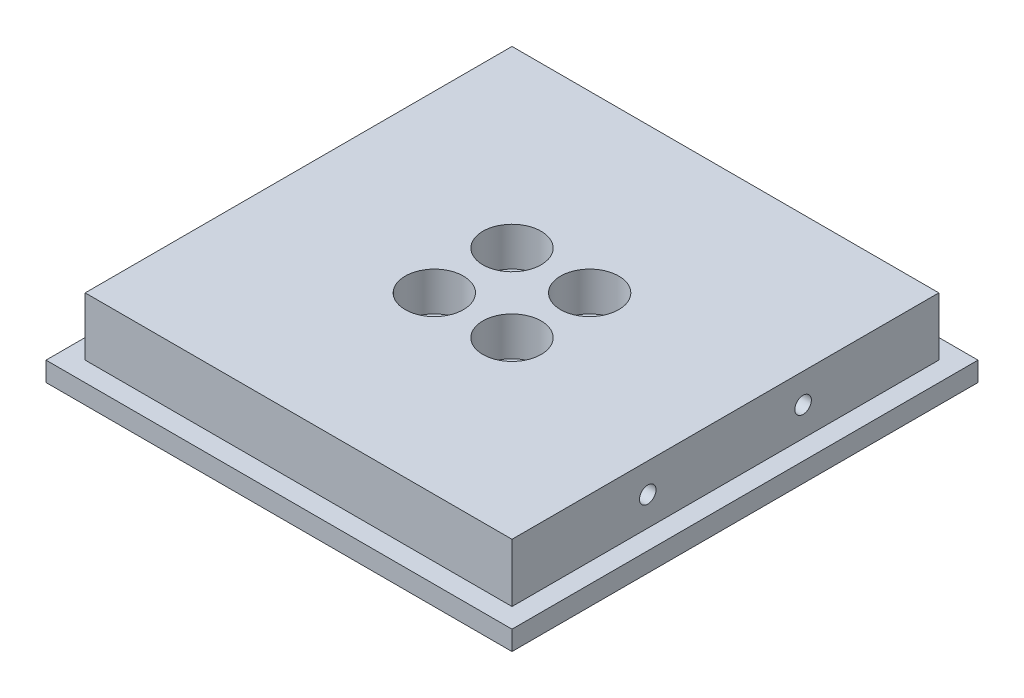
SolidWorks part; units mm, degrees
material "6061-T6 (SS)"
ref_plane "Front Plane" through (0, 0, 0) normal (0, 0, 1) x (1, 0, 0)
ref_plane "Top Plane" through (0, 0, 0) normal (0, 1, 0) x (1, 0, 0)
ref_plane "Right Plane" through (0, 0, 0) normal (1, 0, 0) x (0, 0, -1)
sketch "Sketch1" plane through (0, 0, 0) normal (0, 1, 0) x (1, 0, 0)
  line L1 (-38.1, -38.1) -> (38.1, -38.1)
  line L2 (-38.1, -38.1) -> (-38.1, 38.1)
  line L3 (-38.1, 38.1) -> (38.1, 38.1)
  line L4 (38.1, -38.1) -> (38.1, 38.1)
  line L5 (-38.1, -38.1) -> (38.1, 38.1) construction
  line L6 (-38.1, 38.1) -> (38.1, -38.1) construction
  point P0 (0, 0)
  dimension "D1" = 76.2
  dimension "D2" = 76.2
extrude "Boss-Extrude1" add sketch "Sketch1" along normal blind 3.175
sketch "Sketch2" plane through (0, 3.175, 0) normal (0, 1, 0) x (1, 0, 0)
  line L0 (-38.1, 38.1) -> (-38.1, -38.1) construction
  line L1 (34.8971, -34.8971) -> (-34.8971, -34.8971)
  line L2 (34.8971, -34.8971) -> (34.8971, 34.8971)
  line L3 (34.8971, 34.8971) -> (-34.8971, 34.8971)
  line L4 (-34.8971, -34.8971) -> (-34.8971, 34.8971)
  line L5 (34.8971, -34.8971) -> (-34.8971, 34.8971) construction
  line L6 (34.8971, 34.8971) -> (-34.8971, -34.8971) construction
  line L7 (28.5471, -28.5471) -> (-28.5471, -28.5471)
  line L8 (28.5471, -28.5471) -> (28.5471, 28.5471)
  line L9 (28.5471, 28.5471) -> (-28.5471, 28.5471)
  line L10 (-28.5471, -28.5471) -> (-28.5471, 28.5471)
  line L11 (28.5471, -28.5471) -> (-28.5471, 28.5471) construction
  line L12 (28.5471, 28.5471) -> (-28.5471, -28.5471) construction
  line L14 (38.1, 38.1) -> (-38.1, 38.1) construction
  point P0 (0, 0)
  point P6 (0, 0)
  dimension "D1" = 3.2029
  dimension "D2" = 3.2029
  dimension "D3" = 6.35
extrude "Boss-Extrude2" add sketch "Sketch2" along normal blind 9.525 contours L10 L7 L8 L9 | L4 L1 L2 L3 L7 L10 L9 L8
sketch "Sketch8" plane through (34.8971, 0, 0) normal (1, 0, 0) x (0, 0, -1)
  line L0 (-38.1, 3.175) -> (38.1, 3.175) construction
  point P0 (-12.7, 7.9375)
  dimension "D1" = 4.7625
  dimension "D2" = 12.7
hole_wizard "#6-32 Tapped Hole2" positions "Sketch10" profile "Sketch9" tap size "#6-32" standard "ANSI Inch"
sketch "Sketch10" plane through (34.8971, 0, 0) normal (1, 0, 0) x (0, 0, -1)
  point P0 (-12.7, 7.9375)
cosmetic thread "Hole Thread1" parameters "D1"=4.7346, "D2"=3.5052
sketch "Sketch9" plane through (34.8971, 7.9375, 12.7) normal (0, 1, 0) x (0, 0, -1)
  line L0 (0, 0) -> (0, 11.9887)
  line L1 (0, 11.9887) -> (1.3525, 11.176)
  line L2 (1.3525, 11.176) -> (1.3525, 0)
  line L5 (1.3525, 0) -> (0, 0)
  line L10 (0, 11.9887) -> (-1.3526, 11.176) construction
  line L11 (0, -6.35) -> (0, 107.95) construction
  dimension "Tap Drill Dia." = 2.7051
  dimension "Tap Drill Depth" = 11.176
  dimension "Drill Angle" = 118
mirror "Mirror1" about plane through (0, 0, 0) normal (0, 0, 1) of "#6-32 Tapped Hole2"
mirror "Mirror2" about plane through (0, 0, 0) normal (1, 0, 0) of "Mirror1", "#6-32 Tapped Hole2"
sketch "Sketch13" plane through (0, 0, 0) normal (0, -1, 0) x (1, 0, 0)
  line L2 (-12.7, -12.7) -> (12.7, -12.7)
  line L3 (-12.7, -12.7) -> (-12.7, 12.7)
  line L4 (-12.7, 12.7) -> (12.7, 12.7)
  line L7 (12.7, -12.7) -> (12.7, 12.7)
  line L8 (-12.7, -12.7) -> (12.7, 12.7) construction
  line L9 (-12.7, 12.7) -> (12.7, -12.7) construction
  circle A0 centre (-7.9375, 12.7) radius 4.7625
  circle A1 centre (12.7, 7.9375) radius 4.7625
  circle A2 centre (7.9375, -12.7) radius 4.7625
  circle A3 centre (-12.7, -7.9375) radius 4.7625
  point P0 (0, 0)
  dimension "D3" = 9.525
  dimension "D1" = 25.4
  dimension "D2" = 25.4
extrude "Cut-Extrude1" cut sketch "Sketch13" against normal blind 3.175 contours A3 L2 A2 L7 A1 L4 A0 L3 | L7 A1 | L7 A1 | L4 A0 | L4 A0 | L3 A3 | L3 A3 | L2 A2 | L2 A2
sketch "Sketch15" plane through (0, 3.175, 0) normal (0, -1, 0) x (1, 0, 0)
  circle A0 centre (-6.35, 6.35) radius 2.5527
  circle A1 centre (6.35, 6.35) radius 2.5527
  circle A2 centre (6.35, -6.35) radius 2.5527
  circle A3 centre (-6.35, -6.35) radius 2.5527
  point P0 (6.35, 6.35)
  point P1 (6.35, -6.35)
  point P2 (-6.35, 6.35)
  point P3 (-6.35, -6.35)
  dimension "D5" = 5.1054
  dimension "D1" = 6.35
  dimension "D2" = 6.35
  dimension "D3" = 6.35
  dimension "D4" = 6.35
extrude "Cut-Extrude2" cut sketch "Sketch15" against normal through all
sketch "Sketch17" plane through (0, 12.7, 0) normal (0, 1, 0) x (1, 0, 0)
  circle A0 centre (-6.35, 6.35) radius 4.7625
  circle A1 centre (6.35, 6.35) radius 4.7625
  circle A2 centre (6.35, -6.35) radius 4.7625
  circle A3 centre (-6.35, -6.35) radius 4.7625
  dimension "D1" = 9.525
extrude "Cut-Extrude3" cut sketch "Sketch17" against normal blind 6.35
equation "\"D2@Sketch2\"=\"D1@Sketch2\""
equation "\"D2@Sketch1\"=\"D1@Sketch1\""
